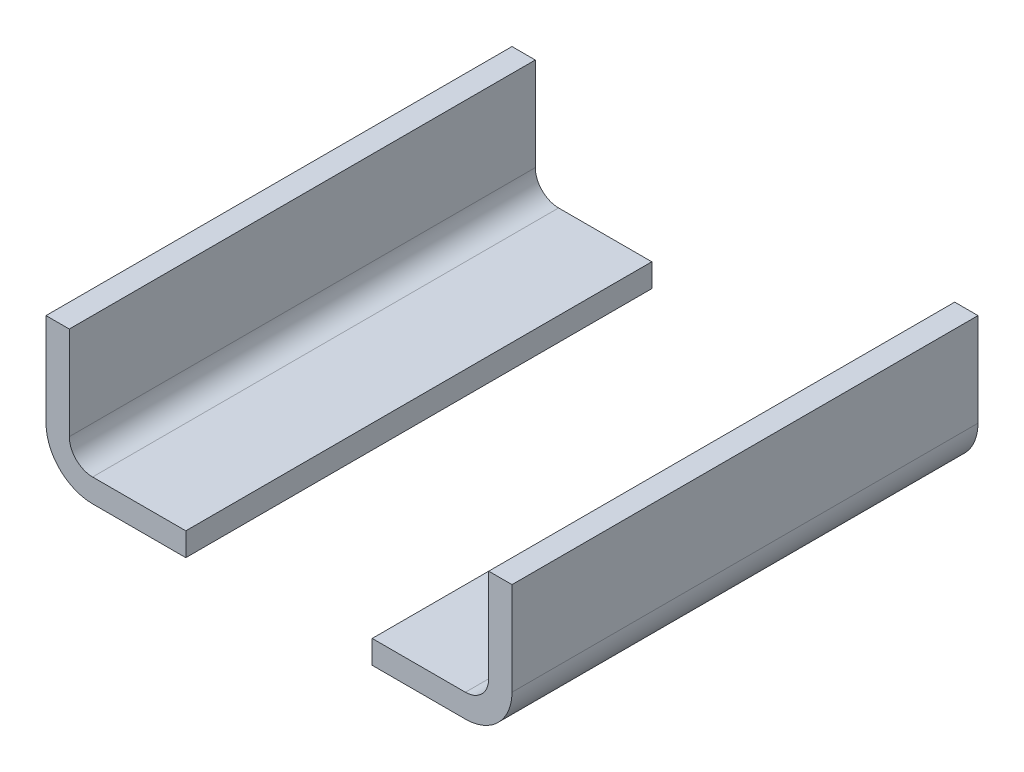
SolidWorks part; units mm, degrees
ref_plane "Alzado" through (0, 0, 0) normal (0, 0, 1) x (1, 0, 0)
ref_plane "Planta" through (0, 0, 0) normal (0, 1, 0) x (1, 0, 0)
ref_plane "Vista lateral" through (0, 0, 0) normal (1, 0, 0) x (0, 0, -1)
sketch "Croquis1" plane through (0, 0, 0) normal (0, 0, 1) x (1, 0, 0)
  line L0 (0, 0) -> (0, 32.9752) construction
  line L7 (-40, 0) -> (-80, 0)
  line L8 (-100, 20) -> (-100, 60)
  line L13 (-40, 10) -> (-80, 10)
  line L14 (-90, 20) -> (-90, 60)
  line L15 (-90, 60) -> (-100, 60)
  line L16 (-40, 0) -> (-40, 10)
  line L17 (40, 0) -> (80, 0)
  line L18 (100, 20) -> (100, 60)
  line L19 (90, 60) -> (100, 60)
  line L20 (90, 20) -> (90, 60)
  line L21 (40, 10) -> (80, 10)
  line L22 (40, 0) -> (40, 10)
  arc A0 (-80, 0) -> (-100, 20) centre (-80, 20) cw
  arc A1 (-80, 10) -> (-90, 20) centre (-80, 20) cw
  arc A2 (80, 0) -> (100, 20) centre (80, 20) ccw
  arc A3 (80, 10) -> (90, 20) centre (80, 20) ccw
  point P10 (-100, 0)
  dimension "D3" = 20
  dimension "D1" = 60
  dimension "D2" = 60
  dimension "D4" = 10
  dimension "D5" = 100
extrude "Saliente-Extruir1" add sketch "Croquis1" along normal blind 200
